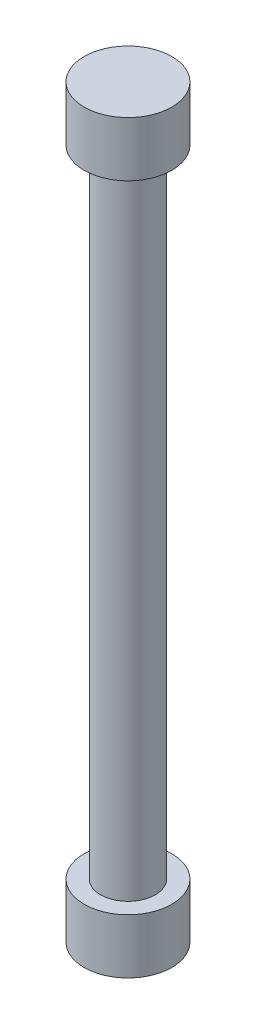
SolidWorks part; units mm, degrees
ref_plane "Front Plane" through (0, 0, 0) normal (0, 0, 1) x (1, 0, 0)
ref_plane "Top Plane" through (0, 0, 0) normal (0, 1, 0) x (1, 0, 0)
ref_plane "Right Plane" through (0, 0, 0) normal (1, 0, 0) x (0, 0, -1)
sketch "Sketch1" plane through (0, 0, 0) normal (0, 1, 0) x (1, 0, 0)
  circle A0 centre (0, 0) radius 2.5
  dimension "D1" = 5
extrude "Boss-Extrude1" add sketch "Sketch1" against normal blind 58
sketch "Sketch2" plane through (0, 0, 0) normal (0, 1, 0) x (1, 0, 0)
  circle A0 centre (0, 0) radius 4
  dimension "D1" = 8
extrude "Boss-Extrude2" add sketch "Sketch2" along normal blind 5
sketch "Sketch3" plane through (0, 0, 0) normal (0, 1, 0) x (1, 0, 0)
  circle A0 centre (0, 0) radius 4
  dimension "D1" = 8
extrude "Boss-Extrude3" add sketch "Sketch3" against normal blind 5 from surface at -58 starting at face at (0, -58, 2.5)
